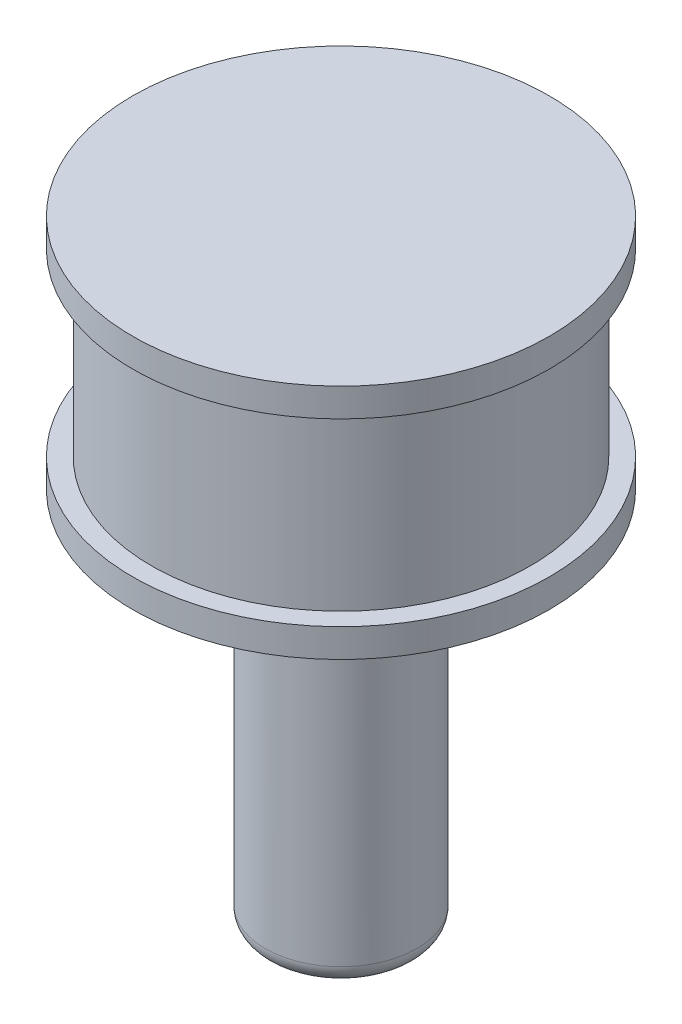
SolidWorks part; units mm, degrees
ref_plane "Front Plane" through (0, 0, 0) normal (0, 0, 1) x (1, 0, 0)
ref_plane "Top Plane" through (0, 0, 0) normal (0, 1, 0) x (1, 0, 0)
ref_plane "Right Plane" through (0, 0, 0) normal (1, 0, 0) x (0, 0, -1)
sketch "Sketch1" plane through (0, 0, 0) normal (0, 0, 1) x (1, 0, 0)
  line L2 (-4, -20) -> (-4, 0)
  line L3 (-4, 0) -> (-11, 0)
  line L4 (-11, 0) -> (-11, 1.5)
  line L5 (-11, 1.5) -> (-10, 1.5)
  line L6 (-10, 1.5) -> (-10, 11)
  line L7 (-10, 11) -> (-11, 11)
  line L8 (-11, 11) -> (-11, 12.5)
  line L9 (-11, 12.5) -> (0, 12.5)
  line L10 (0, 12.5) -> (0, -20)
  line L11 (0, -20) -> (-4, -20)
  point P1 (-4, -12.9937)
  dimension "D1" = 4
  dimension "D2" = 1
  dimension "D3" = 20
  dimension "D4" = 1.5
  dimension "D7" = 12.5
  dimension "D8" = 10
revolve "Revolve1" add sketch "Sketch1" angle 360 about L10
fillet "Fillet1" radius 1 1 edges at (-4, -20, 0)
